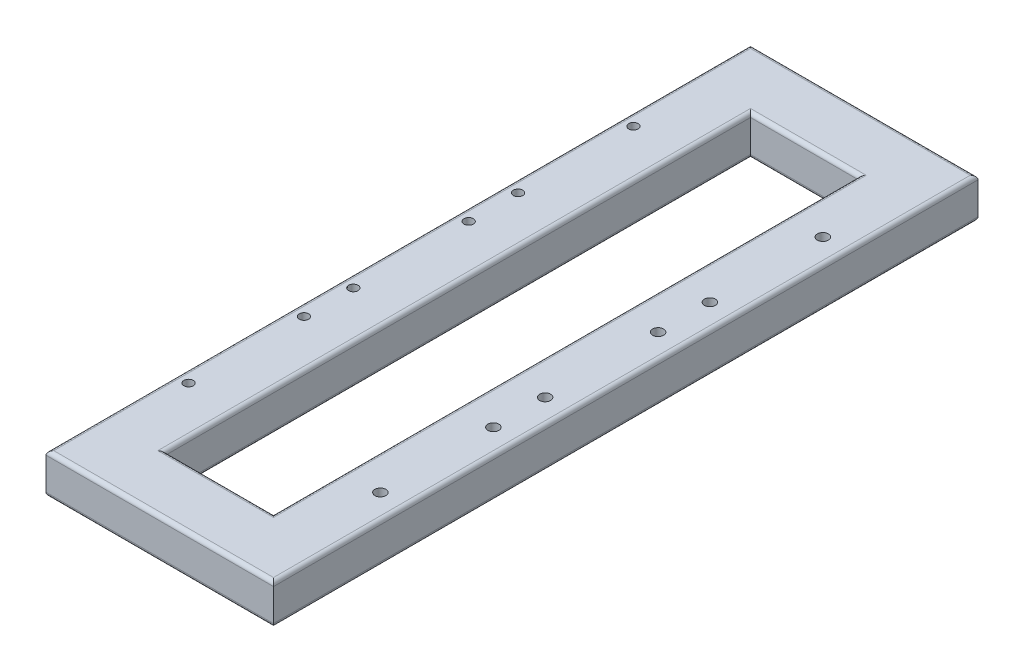
SolidWorks part; units mm, degrees
ref_plane "Alzado" through (0, 0, 0) normal (0, 0, 1) x (1, 0, 0)
ref_plane "Planta" through (0, 0, 0) normal (0, 1, 0) x (1, 0, 0)
ref_plane "Vista lateral" through (0, 0, 0) normal (1, 0, 0) x (0, 0, -1)
sketch "Croquis1" plane through (0, 0, 0) normal (0, 1, 0) x (1, 0, 0)
  line L0 (-273.75, 375.5) -> (-273.75, 312.5) construction
  line L1 (-290, 0) -> (0, 0)
  line L2 (-290, 0) -> (-290, 898)
  line L3 (-290, 898) -> (0, 898)
  line L4 (0, 0) -> (0, 898)
  line L5 (-290, 0) -> (0, 898) construction
  line L6 (-290, 898) -> (0, 0) construction
  line L7 (-213.8, 76.2) -> (-76.2, 76.2)
  line L8 (-213.8, 76.2) -> (-213.8, 821.8)
  line L9 (-213.8, 821.8) -> (-76.2, 821.8)
  line L10 (-76.2, 76.2) -> (-76.2, 821.8)
  line L11 (-213.8, 76.2) -> (-76.2, 821.8) construction
  line L12 (-213.8, 821.8) -> (-76.2, 76.2) construction
  line L13 (-30.75, 377) -> (-30.75, 311) construction
  line L14 (-273.75, 312.5) -> (-273.75, 165.5) construction
  line L15 (-30.75, 311) -> (-30.75, 167) construction
  line L16 (-145, 449) -> (-442.0409, 449) construction
  line L17 (-30.75, 587) -> (-30.75, 731) construction
  line L18 (-273.75, 585.5) -> (-273.75, 732.5) construction
  circle A0 centre (-273.75, 375.5) radius 6
  circle A1 centre (-273.75, 522.5) radius 6
  circle A2 centre (-30.75, 377) radius 7
  circle A3 centre (-30.75, 521) radius 7
  circle A4 centre (-30.75, 167) radius 7
  circle A5 centre (-273.75, 732.5) radius 6
  circle A6 centre (-273.75, 312.5) radius 6
  circle A7 centre (-30.75, 311) radius 7
  circle A8 centre (-273.75, 165.5) radius 6
  circle A9 centre (-30.75, 587) radius 7
  circle A10 centre (-273.75, 585.5) radius 6
  circle A11 centre (-30.75, 731) radius 7
  point P0 (-145, 449)
  point P5 (-145, 449)
  dimension "D3" = 14
  dimension "D4" = 12
  dimension "D7" = 14
  dimension "D15" = 63
  dimension "D16" = 66
  dimension "D17" = 73.5
  dimension "D1" = 63
  dimension "D2" = 66
  dimension "D5" = 147
  dimension "D6" = 144
  dimension "D8" = 290
  dimension "D9" = 898
  dimension "D10" = 76.2
  dimension "D11" = 76.2
  dimension "D12" = 167
  dimension "D13" = 30.75
  dimension "D14" = 16.25
  dimension "D18" = 72
  dimension "D19" = 73.5
  dimension "D20" = 72
extrude "Saliente-Extruir1" add sketch "Croquis1" along normal blind 50.8
fillet "Redondeo1" radius 5 8 edges at (0, 50.8, -449) (-145, 50.8, -898) (-290, 50.8, -449) (-145, 50.8, 0) (-145, 50.8, -76.2) (-76.2, 50.8, -449) (-145, 50.8, -821.8) (-213.8, 50.8, -449)
fillet "Redondeo2" radius 5 8 edges at (-145, 0, -898) (-290, 0, -449) (0, 0, -449) (-145, 0, 0) (-145, 0, -76.2) (-213.8, 0, -449) (-145, 0, -821.8) (-76.2, 0, -449)
sketch "Croquis2" plane through (0, 50.8, 0) normal (0, 1, 0) x (1, 0, 0)
  line L0 (-145, 898) -> (-145, 0) construction
  line L1 (-290, 898) -> (0, 898) construction
  line L2 (0, 0) -> (-290, 0) construction
ref_plane "Plano1" through (-145, 0, 0) normal (-1, 0, 0) x (0, 0, 1)
